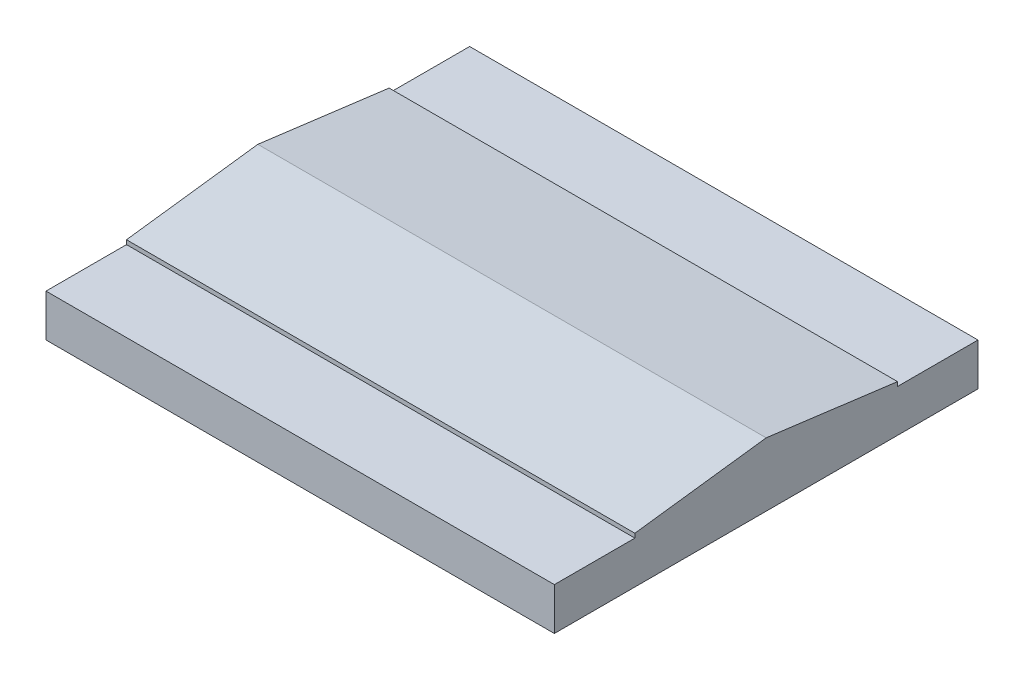
SolidWorks part; units mm, degrees
ref_plane "前视基准面" through (0, 0, 0) normal (0, 0, 1) x (1, 0, 0)
ref_plane "上视基准面" through (0, 0, 0) normal (0, 1, 0) x (1, 0, 0)
ref_plane "右视基准面" through (0, 0, 0) normal (1, 0, 0) x (0, 0, -1)
sketch "草图1" plane through (0, 0, 0) normal (0, 1, 0) x (1, 0, 0)
  line L1 (0, 500) -> (600, 500)
  line L2 (0, 500) -> (0, 0)
  line L3 (0, 0) -> (600, 0)
  line L4 (600, 500) -> (600, 0)
  dimension "D1" = 600
  dimension "D2" = 500
extrude "凸台-拉伸1" add sketch "草图1" along normal blind 75
sketch "草图3" plane through (600, 0, 0) normal (1, 0, 0) x (0, 0, -1)
  line L0 (250, -925) -> (250, 49075) construction
  line L1 (0, 75) -> (500, 75) construction
  line L2 (405, 55) -> (405, 50)
  line L3 (405, 50) -> (500, 50)
  line L4 (500, 75) -> (500, 0) construction
  line L5 (500, 50) -> (500, 75)
  line L6 (500, 75) -> (250, 75)
  line L7 (250, 75) -> (405, 55)
  point P5 (250, 75)
  dimension "D1" = 20
  dimension "D2" = 5
  dimension "D3" = 95
extrude "切除-拉伸1" cut sketch "草图3" against normal through all
sketch "草图4" plane through (600, 0, 0) normal (1, 0, 0) x (0, 0, -1)
  line L0 (250, -1000) -> (250, 49000) construction
  line L1 (0, 0) -> (500, 0) construction
  line L2 (0, 75) -> (250, 75) construction
  line L4 (0, 75) -> (0, 0) construction
  line L5 (0, 75) -> (0, 50)
  line L6 (0, 50) -> (95, 50)
  line L7 (0, 75) -> (250, 75)
  line L8 (95, 50) -> (95, 55)
  line L9 (405, 50) -> (500, 50) construction
  line L10 (95, 55) -> (250, 75)
  point P5 (250, 0)
  dimension "D1" = 95
extrude "切除-拉伸2" cut sketch "草图4" against normal through all
